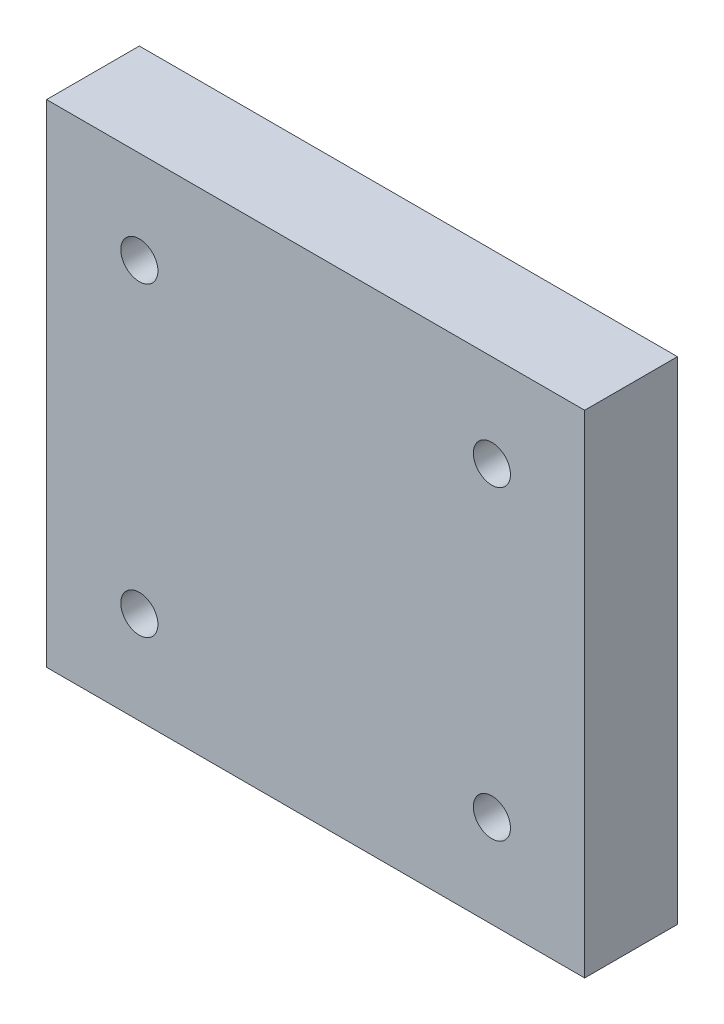
SolidWorks part; units mm, degrees
ref_plane "Front Plane" through (0, 0, 0) normal (0, 0, 1) x (1, 0, 0)
ref_plane "Top Plane" through (0, 0, 0) normal (0, 1, 0) x (1, 0, 0)
ref_plane "Right Plane" through (0, 0, 0) normal (1, 0, 0) x (0, 0, -1)
sketch "Sketch1" plane through (0, 0, 0) normal (0, 0, 1) x (1, 0, 0)
  line L0 (0, 150) -> (180, 150) construction
  line L1 (0, 0) -> (180, 0)
  line L2 (0, 0) -> (0, 300)
  line L3 (0, 300) -> (180, 300) construction
  line L4 (180, 0) -> (180, 300)
  line L5 (0, 300) -> (50, 300)
  line L6 (50, 300) -> (50, 150)
  line L7 (-66, 110) -> (0, 60) construction
  line L8 (0, 110) -> (-66, 110)
  line L9 (0, 110) -> (0, 60)
  line L10 (0, 60) -> (-66, 60)
  line L11 (-66, 110) -> (-66, 60)
  line L12 (0, 110) -> (-66, 60) construction
  line L13 (-33, 85) -> (-66, 85) construction
  line L14 (90, 150) -> (90, 0) construction
  line L15 (180, 110) -> (246, 110)
  line L16 (180, 110) -> (246, 60) construction
  line L17 (246, 110) -> (180, 60) construction
  line L18 (180, 60) -> (246, 60)
  line L19 (213, 85) -> (246, 85) construction
  line L20 (246, 110) -> (246, 60)
  line L21 (11, 117.5) -> (46, 117.5) construction
  line L22 (50, 150) -> (85, 150) construction
  line L23 (50, 150) -> (50, 110) construction
  line L24 (50, 110) -> (85, 110) construction
  line L25 (85, 150) -> (85, 110) construction
  line L26 (11, 150) -> (46, 150) construction
  line L27 (11, 150) -> (11, 110) construction
  line L28 (11, 110) -> (46, 110) construction
  line L29 (46, 150) -> (46, 110) construction
  line L30 (11, 134) -> (46, 134) construction
  line L31 (19, 150) -> (19, 110) construction
  line L32 (38, 150) -> (38, 110) construction
  line L33 (50, 150) -> (130, 150)
  line L34 (130, 300) -> (130, 150)
  line L35 (180, 300) -> (130, 300)
  circle A0 centre (19, 134) radius 1
  circle A1 centre (38, 134) radius 1
  circle A2 centre (19, 117.5) radius 1
  circle A3 centre (38, 117.5) radius 1
  circle A4 centre (161, 117.5) radius 1
  circle A5 centre (142, 117.5) radius 1
  circle A6 centre (142, 134) radius 1
  circle A7 centre (161, 134) radius 1
  point P7 (90, 150)
  dimension "D17" = 2
  dimension "D18" = 2
  dimension "D19" = 2
  dimension "D20" = 2
  dimension "D1" = 180
  dimension "D2" = 300
  dimension "D3" = 150
  dimension "D4" = 156
  dimension "D5" = 50
  dimension "D6" = 85
  dimension "D7" = 35
  dimension "D8" = 5
  dimension "D9" = 40
  dimension "D10" = 40
  dimension "D11" = 4
  dimension "D12" = 35
  dimension "D13" = 7.5
  dimension "D14" = 24
  dimension "D15" = 8
  dimension "D16" = 8
extrude "Boss-Extrude1" add sketch "Sketch1" along normal blind 5
sketch "Sketch2" plane through (0, 0, 5) normal (0, 0, 1) x (1, 0, 0)
  line L0 (-66, 110) -> (-66, 60) construction
  line L1 (-66, 110) -> (-51, 110) construction
  line L2 (-66, 110) -> (-66, 60) construction
  line L3 (-66, 60) -> (-51, 60) construction
  line L4 (-51, 110) -> (-51, 60) construction
  line L5 (0, 60) -> (-66, 60) construction
  line L6 (-58, 110) -> (-58, 60) construction
  line L7 (90, 150) -> (90, 0) construction
  line L8 (0, 0) -> (180, 0) construction
  line L9 (50, 150) -> (130, 150) construction
  circle A0 centre (-58, 103) radius 1
  circle A1 centre (-58, 67) radius 1
  circle A2 centre (238, 67) radius 1
  circle A3 centre (238, 103) radius 1
  dimension "D4" = 2
  dimension "D5" = 7
  dimension "D7" = 2
  dimension "D1" = 50
  dimension "D2" = 15
  dimension "D3" = 7
  dimension "D6" = 7
extrude "Cut-Extrude1" cut sketch "Sketch2" against normal through all
sketch "Sketch3" plane through (0, 0, 5) normal (0, 0, 1) x (1, 0, 0)
  line L0 (-16, 92.5) -> (4, 87.5) construction
  line L1 (-16, 92.5) -> (4, 92.5)
  line L2 (-16, 92.5) -> (-16, 87.5)
  line L3 (-16, 87.5) -> (4, 87.5) construction
  line L4 (4, 92.5) -> (4, 87.5)
  line L5 (-16, 87.5) -> (4, 92.5) construction
  line L6 (19, 74.5) -> (19, 99.5) construction
  line L7 (-66, 110) -> (-66, 60) construction
  line L8 (0, 110) -> (-66, 110) construction
  line L9 (-16, 74.5) -> (4, 74.5) construction
  line L10 (-16, 87.5) -> (4, 87.5)
  line L11 (-16, 87.5) -> (-16, 37.5) construction
  line L12 (-16, 37.5) -> (4, 37.5) construction
  line L13 (4, 87.5) -> (4, 37.5) construction
  line L14 (4, 74.5) -> (19, 74.5) construction
  line L15 (90, 0) -> (90, 150) construction
  line L16 (0, 0) -> (180, 0) construction
  line L17 (50, 150) -> (130, 150) construction
  line L18 (196, 92.5) -> (196, 87.5)
  line L19 (196, 87.5) -> (176, 87.5)
  line L20 (176, 92.5) -> (176, 87.5)
  line L21 (196, 92.5) -> (176, 92.5)
  circle A0 centre (19, 77) radius 1
  circle A1 centre (19, 99.5) radius 1
  circle A2 centre (161, 77) radius 1
  circle A3 centre (161, 99.5) radius 1
  point P4 (-6, 90)
  dimension "D9" = 2
  dimension "D10" = 2
  dimension "D11" = 5
  dimension "D1" = 60
  dimension "D2" = 20
  dimension "D3" = 20
  dimension "D4" = 5
  dimension "D5" = 50
  dimension "D6" = 13
  dimension "D7" = 15
  dimension "D8" = 25
extrude "Cut-Extrude2" cut sketch "Sketch3" against normal through all
sketch "Sketch4" plane through (0, 0, 5) normal (0, 0, 1) x (1, 0, 0)
  line L0 (180, 60) -> (130, 60)
  line L1 (130, 150) -> (130, 60)
  line L2 (180, 60) -> (198.3212, 8.7539)
  line L3 (198.3212, 8.7539) -> (175.3321, -20.8591)
  line L4 (175.3321, -20.8591) -> (-107.9394, -9.1698)
  line L5 (-107.9394, -9.1698) -> (-51.0513, 321.2487)
  line L6 (-51.0513, 321.2487) -> (65.0628, 311.8973)
  line L7 (65.0628, 311.8973) -> (130, 150)
extrude "Cut-Extrude3" cut sketch "Sketch4" against normal through all
sketch "Sketch5" plane through (0, 0, 0) normal (0, 0, -1) x (-1, 0, 0)
  line L0 (-161, 117.5) -> (-142, 134) construction
  line L1 (-142, 134) -> (-142, 117.5) construction
  line L2 (-142, 117.5) -> (-161, 134) construction
  line L4 (-166, 112.5) -> (-137, 112.5)
  line L5 (-166, 112.5) -> (-166, 139)
  line L6 (-166, 139) -> (-137, 139)
  line L7 (-137, 112.5) -> (-137, 139)
  line L8 (-166, 112.5) -> (-137, 139) construction
  line L9 (-166, 139) -> (-137, 112.5) construction
  point P4 (-151.5, 125.75)
  dimension "D1" = 5
  dimension "D2" = 5
extrude "Cut-Extrude4" cut sketch "Sketch5" against normal through all flip side to cut
